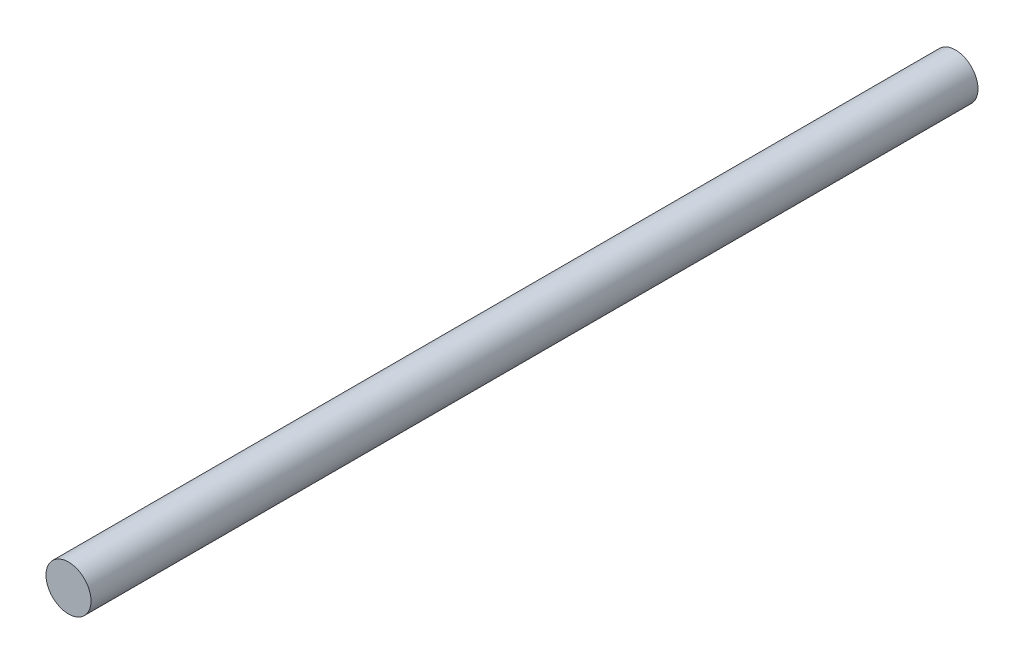
SolidWorks part; units mm, degrees
ref_plane "Front Plane" through (0, 0, 0) normal (0, 0, 1) x (1, 0, 0)
ref_plane "Top Plane" through (0, 0, 0) normal (0, 1, 0) x (1, 0, 0)
ref_plane "Right Plane" through (0, 0, 0) normal (1, 0, 0) x (0, 0, -1)
sketch "Sketch1" plane through (0, 0, 0) normal (0, 0, 1) x (1, 0, 0)
  circle A0 centre (0, 0) radius 1.9844
  dimension "D1" = 3.9688
extrude "Boss-Extrude1" add sketch "Sketch1" along normal blind 78.1253
